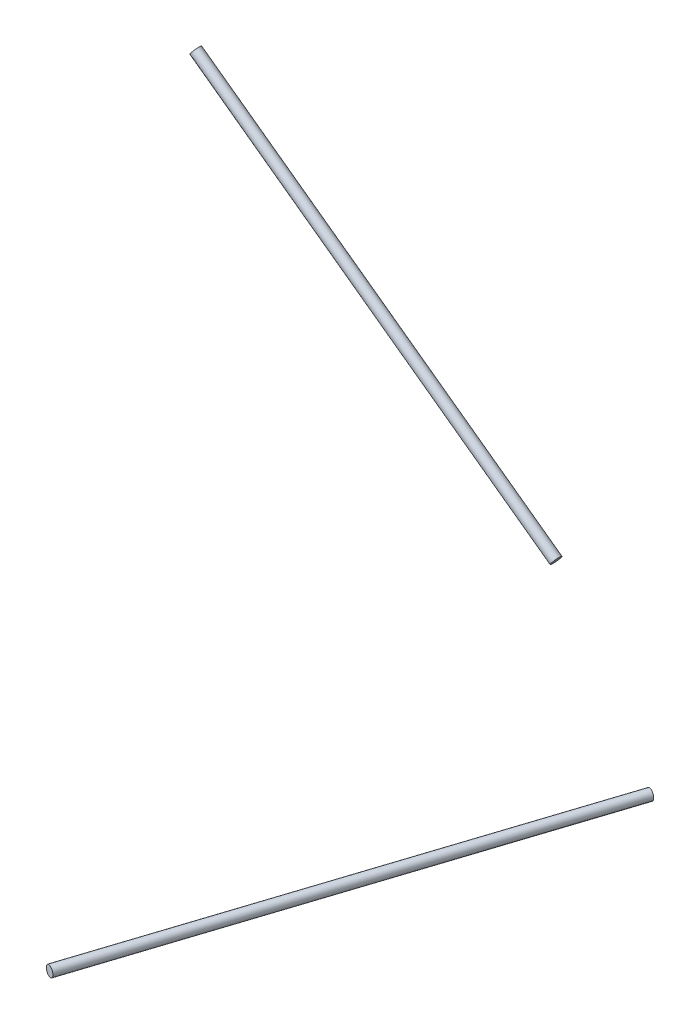
SolidWorks part; units mm, degrees
ref_plane "Front Plane" through (0, 0, 0) normal (0, 0, 1) x (1, 0, 0)
ref_plane "Top Plane" through (0, 0, 0) normal (0, 1, 0) x (1, 0, 0)
ref_plane "Right Plane" through (0, 0, 0) normal (1, 0, 0) x (0, 0, -1)
sketch "Sketch2" plane through (0, 0, 0) normal (0, 0, 1) x (1, 0, 0)
  line L0 (178.7928, 134.6028) -> (72.7649, 211.6366)
  line L1 (182.0288, -132.2517) -> (225, 0) construction
  line L2 (225, 0) -> (182.0288, 132.2517) construction
  line L3 (182.0288, 132.2517) -> (69.5288, 213.9877) construction
  line L4 (69.5288, 213.9877) -> (-69.5288, 213.9877) construction
  line L5 (-69.5288, 213.9877) -> (-182.0288, 132.2517) construction
  line L6 (-182.0288, 132.2517) -> (-225, 0) construction
  line L7 (-225, 0) -> (-182.0288, -132.2517) construction
  line L8 (-182.0288, -132.2517) -> (-69.5288, -213.9877) construction
  line L9 (-69.5288, -213.9877) -> (69.5288, -213.9877) construction
  line L10 (69.5288, -213.9877) -> (182.0288, -132.2517) construction
  line L11 (112.5, 81.736) -> (69.5288, 213.9877) construction
  line L12 (69.5288, 213.9877) -> (-69.5288, 213.9877) construction
  line L13 (-69.5288, 213.9877) -> (-112.5, 81.736) construction
  line L14 (-112.5, 81.736) -> (0, 0) construction
  line L15 (0, 0) -> (112.5, 81.736) construction
  circle A0 centre (0, 0) radius 225 construction
  circle A1 centre (0, 0) radius 213.9877 construction
  circle A2 centre (0, 118.2895) radius 95.6982 construction
  point P16 (0, 225)
  point P24 (0, 213.9877)
  dimension "D1" = 450
  dimension "D2" = 4
  dimension "D3" = 4
ref_plane "Plane1" through (72.7649, 211.6366, 0) normal (-0.809, 0.5878, 0) x (0, 0, 1)
sketch "Sketch3" plane through (72.7649, 211.6366, 0) normal (-0.809, 0.5878, 0) x (0, 0, 1)
  circle A0 centre (0, 0) radius 1.5
  dimension "D1" = 3
sweep "Sweep1" add profiles "Sketch3" path "Sketch2"
sketch "Sketch4" plane through (0, 0, 0) normal (0, 1, 0) x (1, 0, 0)
  line L0 (74.325, -44.5904) -> (117.6888, 88.8696)
ref_plane "Plane2" through (74.325, 0, 44.5904) normal (0.309, 0, -0.9511) x (-0.9511, 0, -0.309)
sketch "Sketch5" plane through (74.325, 0, 44.5904) normal (0.309, 0, -0.9511) x (-0.9511, 0, -0.309)
  circle A0 centre (0, 0) radius 1.5
  dimension "D1" = 3
sweep "Sweep2" add profiles "Sketch5" path "Sketch4"
